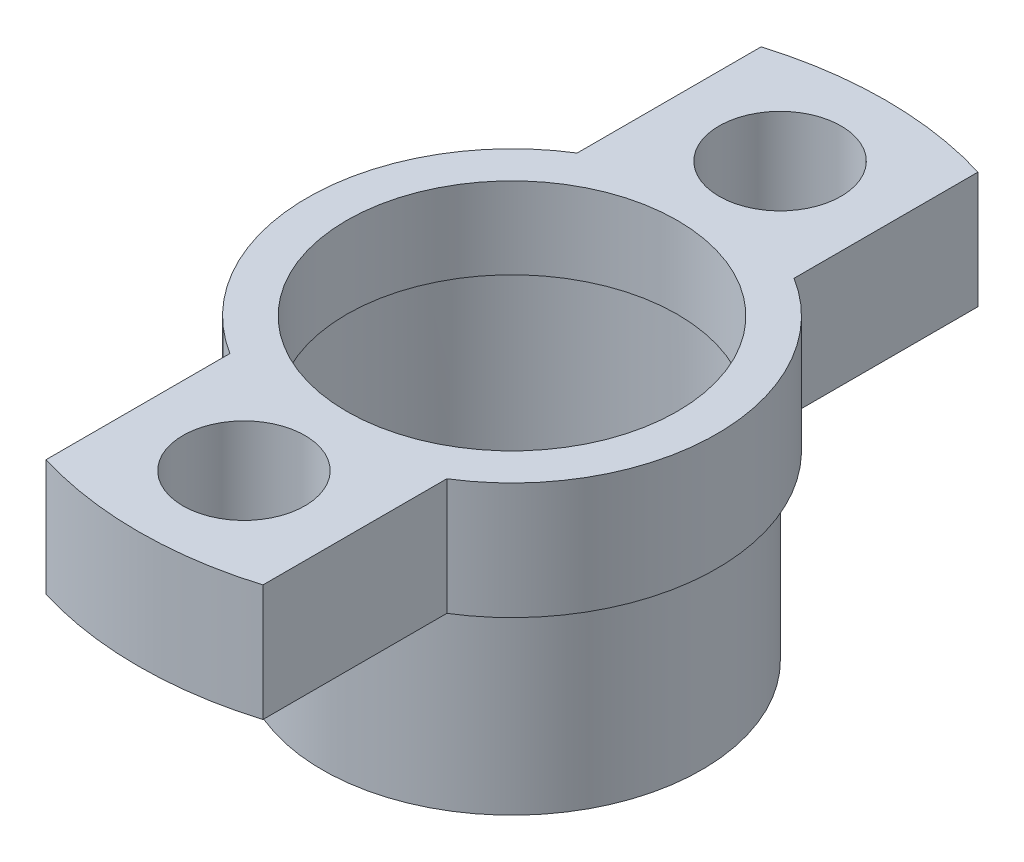
SolidWorks part; units mm, degrees
material "ABS"
ref_plane "Front Plane" through (0, 0, 0) normal (0, 0, 1) x (1, 0, 0)
ref_plane "Top Plane" through (0, 0, 0) normal (0, 1, 0) x (1, 0, 0)
ref_plane "Right Plane" through (0, 0, 0) normal (1, 0, 0) x (0, 0, -1)
sketch "Sketch2" plane through (0, 0, 0) normal (0, 1, 0) x (1, 0, 0)
  circle A0 centre (0, 0) radius 6.55
  circle A1 centre (0, 0) radius 5.8
  dimension "D1" = 13.1
  dimension "D2" = 0.75
extrude "Middle-core" add sketch "Sketch2" along normal blind 6 separate body
ref_plane "Plane for arms" through (0, 5, 0) normal (0, 1, 0) x (1, 0, 0)
sketch "Sketch3" plane through (0, 5, 0) normal (0, 1, 0) x (1, 0, 0)
  line L6 (-4, 5.1868) -> (-4, 13.1868)
  line L7 (-4, 13.1868) -> (4, 13.1868) construction
  line L8 (4, 13.1868) -> (4, 5.1868)
  line L9 (4, -5.1868) -> (4, -13.1868)
  line L10 (4, -13.1868) -> (-4, -13.1868) construction
  line L11 (-4, -13.1868) -> (-4, -5.1868)
  line L12 (0, -13.1868) -> (0, 13.1868) construction
  line L13 (0, -9.8868) -> (0, -13.1868) construction
  line L14 (0, 13.1868) -> (0, 9.8868) construction
  line L15 (0, 7.6368) -> (0, 6.5868) construction
  line L16 (0, 6.5868) -> (0, 12.1368) construction
  line L17 (0, 12.1368) -> (0, 13.1868) construction
  circle A1 centre (0, 9.8868) radius 2.25
  circle A3 centre (0, 0) radius 5.8
  arc A4 (4, -13.1868) -> (-4, -13.1868) centre (0, 0) cw
  arc A5 (-4, 5.1868) -> (-4, -5.1868) centre (0, 0) ccw
  circle A6 centre (0, 0) radius 6.55 construction
  arc A7 (4, -5.1868) -> (4, 5.1868) centre (0, 0) ccw
  circle A8 centre (0, -9.8868) radius 2.25
  circle A10 centre (0, 0) radius 5.8 construction
  arc A11 (-4, 13.1868) -> (4, 13.1868) centre (0, 0) cw
  point P3 (0, 9.8868)
  point P14 (0, 12.1368)
  point P16 (0, 7.6368)
  point P18 (0, -9.8868)
  point P26 (0, -12.1368)
  point P27 (0, -7.6368)
  point P29 (0, 6.5868)
  dimension "D2" = 4.5
  dimension "D1" = 8
  dimension "D3" = 3.3
extrude "Arms_insert-Fixing to guide part" add sketch "Sketch3" against normal blind 4.3
sketch "Sketch1" [suppressed] plane through (0, 0, 0) normal (0, 1, 0) x (1, 0, 0)
  line L0 (-6.2372, -2) -> (-10.2372, -2) construction
  line L1 (-10.2372, -2) -> (-10.2372, 2) construction
  line L2 (-10.2372, 2) -> (-6.2372, 2) construction
  line L3 (6.2372, 2) -> (10.2372, 2) construction
  line L4 (10.2372, 2) -> (10.2372, -2) construction
  line L5 (10.2372, -2) -> (6.2372, -2) construction
  line L6 (-6.55, 0) -> (-10.2372, 0) construction
  line L7 (-6.55, 0) -> (-3.55, 0) construction
  line L8 (-3.55, 0) -> (0, 0) construction
  line L9 (0, 0) -> (3.55, 0) construction
  line L10 (3.55, 0) -> (6.55, 0) construction
  line L11 (6.55, 0) -> (10.2372, 0) construction
  line L13 (-4, -2.1685) -> (-4, 2.1685)
  line L14 (-4, 2.1685) -> (4, 2.1685) construction
  line L15 (4, 2.1685) -> (4, -2.1685)
  line L16 (4, -5.1868) -> (4, -13.1868) construction
  line L17 (-4, -13.1868) -> (-4, -5.1868) construction
  line L18 (-4, -2.1685) -> (-4, -3.8474)
  line L19 (4, -2.1685) -> (4, -3.8474)
  line L20 (-4, 2.1685) -> (-4, 3.8474)
  line L21 (4, 2.1685) -> (4, 3.8474)
  circle A2 centre (0, 0) radius 6.55
  arc A3 (-6.2372, 2) -> (6.2372, 2) centre (0, 0) cw construction
  arc A4 (6.2372, -2) -> (-6.2372, -2) centre (0, 0) cw construction
  arc A5 (-4, -2.1685) -> (-4, 2.1685) centre (0, 0) cw construction
  arc A6 (4, 2.1685) -> (4, -2.1685) centre (0, 0) cw construction
  arc A7 (-4, -3.8474) -> (4, -3.8474) centre (0, 0) ccw
  arc A8 (-4, 3.8474) -> (4, 3.8474) centre (0, 0) cw
  point P15 (10.2372, 0)
  point P20 (-10.2372, 0)
  dimension "D4" = 5.55
  dimension "D1" = 13.1
  dimension "D2" = 4
  dimension "D3" = 4
  dimension "D5" = 1
extrude "Base-hole&toe" [suppressed] add sketch "Sketch1" along normal blind 2
ref_plane "Plane4" [suppressed] through (0, 2, 0) normal (0, 1, 0) x (1, 0, 0)
sketch "Sketch21" [suppressed] plane through (0, 2, 0) normal (0, 1, 0) x (1, 0, 0)
  line L1 (0, 0) -> (3.55, 0) construction
  line L2 (4.0623, -3) -> (12.55, -3)
  line L3 (12.55, -3) -> (12.55, 3)
  line L4 (12.55, 3) -> (4.0623, 3)
  line L5 (-4.0623, 3) -> (-12.55, 3)
  line L6 (-12.55, 3) -> (-12.55, -3)
  line L7 (-12.55, -3) -> (-4.0623, -3)
  line L8 (-12.55, 0) -> (-6.55, 0) construction
  line L9 (-9.55, 3) -> (-9.55, -3) construction
  line L10 (6.55, 0) -> (12.55, 0) construction
  line L11 (9.55, 3) -> (9.55, -3) construction
  line L14 (-6.55, 0) -> (-10.2372, 0) construction
  arc A0 (4.0623, -3) -> (4.0623, 3) centre (0, 0) ccw
  arc A1 (-4.0623, -3) -> (-4.0623, 3) centre (0, 0) cw
  circle A3 centre (-9.55, 0) radius 2
  circle A4 centre (9.55, 0) radius 2
  circle A7 centre (0, 0) radius 6.55 construction
  point P6 (-5.05, 0)
  point P38 (-11.55, 0)
extrude "Arms_hole-Fixing to support part" [suppressed] add sketch "Sketch21" against normal blind 2 separate body
sketch "Sketch22" plane through (0, 5, 0) normal (0, 1, 0) x (1, 0, 0)
  circle A0 centre (0, 0) radius 5.8
  circle A1 centre (0, 0) radius 5.3
  circle A2 centre (0, 0) radius 5.8 construction
  dimension "D1" = 10.6
extrude "Boss-Extrude1" [suppressed] add sketch "Sketch22" along normal up to surface (1 mm away)
sketch "Esquisse1" [suppressed] plane through (0, 0, 0) normal (1, 0, 0) x (0, 0, -1)
  line L1 (-21.6514, 20.4403) -> (22.7117, 20.4403)
  line L2 (-21.6514, 20.4403) -> (-21.6514, -7.7246)
  line L3 (-21.6514, -7.7246) -> (22.7117, -7.7246)
  line L4 (22.7117, 20.4403) -> (22.7117, -7.7246)
extrude "Enlèv. mat.-Extru.1" [suppressed] cut sketch "Esquisse1" along normal through all
sketch "Esquisse2" plane through (0, 0, 0) normal (0, -1, 0) x (1, 0, 0)
  circle A1 centre (0, 0) radius 7.55
  circle A3 centre (0, 0) radius 6.55
  circle A4 centre (0, 0) radius 6.55 construction
  dimension "D1" = 1
extrude "Boss.-Extru.1" add sketch "Esquisse2" against normal up to surface (5 mm away) up to face at (0, 5, -7.6368)
sketch "Esquisse3" plane through (0, 0, 0) normal (0, -1, 0) x (1, 0, 0)
  circle A0 centre (0, 0) radius 6.65
  circle A1 centre (0, 0) radius 7.55
  circle A2 centre (0, 0) radius 7.55 construction
  dimension "D1" = 0.9
extrude "Boss.-Extru.2" add sketch "Esquisse3" along normal blind 6
sketch "Esquisse4" plane through (0, 0.7, 0) normal (0, -1, 0) x (1, 0, 0)
  circle A0 centre (0, -9.8868) radius 2.75
  circle A1 centre (0, 9.8868) radius 2.75
  circle A2 centre (0, 9.8868) radius 2.25 construction
  circle A3 centre (0, 9.8868) radius 2.25 construction
  circle A4 centre (0, -9.8868) radius 2.25 construction
  dimension "D1" = 0.5
extrude "Enlèv. mat.-Extru.2" cut sketch "Esquisse4" along normal blind 4
sketch "Sketch23" [suppressed] plane through (0, -6, 0) normal (0, -1, 0) x (1, 0, 0)
  line L0 (25, 25) -> (-25, -25) construction
  line L1 (25, 25) -> (-25, 25)
  line L2 (25, 25) -> (25, -25)
  line L3 (25, -25) -> (-25, -25)
  line L4 (-25, 25) -> (-25, -25)
  line L5 (25, -25) -> (-25, 25) construction
  circle A0 centre (0, 0) radius 7.55
  circle A2 centre (0, 0) radius 7.55 construction
  point P9 (0, 0)
  dimension "D1" = 50
extrude "Cut-Extrude1" [suppressed] cut sketch "Sketch23" against normal blind 4
sketch "Sketch25" [suppressed] plane through (0, 0, 0) normal (0, 1, 0) x (1, 0, 0)
  circle A0 centre (11.5717, 8.8388) radius 7.8078
extrude "Cut-Extrude2" [suppressed] cut sketch "Sketch25" against normal through all both and the other way through all
sketch "Sketch26" plane through (0, -6, 0) normal (0, -1, 0) x (1, 0, 0)
  circle A0 centre (0, 0) radius 7.55
  circle A1 centre (0, 0) radius 6.65
extrude "Boss-Extrude4" add sketch "Sketch26" against normal up to surface (6.7 mm away) up to face at (0, 0.7, 9.1037)
sketch "Sketch27" plane through (0, -6, 0) normal (0, -1, 0) x (1, 0, 0)
  circle A0 centre (0, 0) radius 7.55
  circle A1 centre (0, 0) radius 7
  dimension "D1" = 14
extrude "Cut-Extrude3" cut sketch "Sketch27" against normal up to surface (6.7 mm away) up to face at (0, 0.7, 10.23)
sketch "Sketch28" plane through (0, -6, 0) normal (0, -1, 0) x (1, 0, 0)
  circle A0 centre (0, 0) radius 6.65
extrude "Cut-Extrude5" cut sketch "Sketch28" against normal blind 30
sketch "Sketch29" plane through (0, 5, 0) normal (0, 1, 0) x (1, 0, 0)
  circle A0 centre (0, 0) radius 6.65
  circle A1 centre (0, 0) radius 5.6
extrude "Boss-Extrude5" add sketch "Sketch29" against normal blind 3
sketch "Sketch30" plane through (0, 5, 0) normal (0, 1, 0) x (1, 0, 0)
  circle A0 centre (0, 0) radius 5.65
  dimension "D1" = 11.3
extrude "Cut-Extrude6" cut sketch "Sketch30" against normal blind 12
sketch "Sketch31" plane through (0, 2, 0) normal (0, -1, 0) x (1, 0, 0)
  circle A0 centre (0, 0) radius 5.675
  dimension "D1" = 11.35
extrude "Cut-Extrude7" cut sketch "Sketch31" against normal blind 10
sketch "Sketch32" plane through (0, 0.7, 0) normal (0, -1, 0) x (1, 0, 0)
  circle A0 centre (0, 0) radius 7.55
sketch "Sketch34" plane through (0, 5, 0) normal (0, 1, 0) x (1, 0, 0)
  circle A0 centre (0, 0) radius 6.1
  dimension "D1" = 12.2
extrude "Cut-Extrude9" cut sketch "Sketch34" against normal blind 10
equation "\"magnet_DI\"= 3mm'inner diameter of the o-ring magnet"
equation "\"magnet_DE\"= 8mm'external diameter of the o-ring magnet"
equation "\"magnet_H\"= 3mm'tall of the magnet"
equation "\"magnet_levitation_DI\"= 0mm'inner diameter of the o-ring magnet"
equation "\"magnet_levitation_DE\"= 1mm'external diameter of the o-ring magnet"
equation "\"magnet_levitation_H\"= 0.5mm'tall of the magnet"
equation "\"gap_magnet_H\"= 1mm'gap between the 2 magnets"
equation "\"plug_DI\"= 1.5mm'size of the inner extrude of the plug (finger contact)"
equation "\"coil_H\"= 8mm 'height coil"
equation "\"coil_W\"= 0.2mm 'width coil"
equation "\"mandrine_freegap\"= 0.2mm 'gap between the magnet and the mandrine. "
equation "\"mandrine_bottom_H\"= 0.5mm 'border of the bottom of the mandrine"
equation "\"mandrine_coilmagnet_wall\"= 0.15mm"
equation "\"mandrine_magnet_lev\"= 3mm' gap needed for the levitation of the rod"
equation "\"mandrine_border_H\"= 2mm 'border of the top of the mandrine"
equation "\"mandrine_epoxy_W\"= 0.5mm 'width epoxy"
equation "\"mandrine_DI\"= \"mandrine_freegap\"*2+\"magnet_DE\""
equation "\"mandrine_DE\"= (\"mandrine_epoxy_W\"+\"coil_W\"+\"mandrine_coilmagnet_wall\")*2+\"mandrine_DI\""
equation "\"mandrine_H\"= \"magnet_levitation_H\"+\"mandrine_magnet_lev\"+\"magnet_H\"+\"gap_magnet_H\"/2+\"coil_H\"/2+\"mandrine_border_H\""
equation "\"mandrine_hat_W\"= 1mm"
equation "\"tower_freegap\"= 1mm 'gap between the actuator and the tower"
equation "\"tower_DI\"= \"mandrine_DE\"+\"tower_freegap\""
equation "\"tower_W\"= 1mm'width of the tower"
equation "\"tower_link_H\"= 2mm"
equation "\"tower_link_W\"= 4mm"
equation "\"tower_channel_W\"= 1mm"
equation "\"tower_renforcement_H\"= 2mm"
equation "\"apex_tower_Dbase\"= 2.5mm 'diameter of the holes in order to curve"
equation "\"apex_tower_Rbase1\"= 0.75mm 'diameter of the holes in order to curve"
equation "\"apex_tower_Rbase2\"= 1mm 'diameter of the holes in order to curve"
equation "\"apex_tower_Rbase3\"= 1.25mm 'diameter of the holes in order to curve"
equation "\"apex_tower_holeOpening1\"= \"apex_tower_Rbase1\"*7/8"
equation "\"apex_tower_holeOpening2\"= \"apex_tower_Rbase2\"*7/8"
equation "\"apex_tower_holeOpening3\"= \"apex_tower_Rbase3\"*7/8"
equation "\"apex_tower_Hbase\"= 1mm 'gap between the bottom of the tower and the holes"
equation "\"apex_tower_hole\"= 4.5mm 'witdh of the hole"
equation "\"apex_tower_H\"= 0mm '\"mandrine_H\"-\"tower_link_H\""
equation "\"apex_tower_H2\"= \"apex_tower_H\"+7mm"
equation "\"actuator1.x\"= 42.59mm"
equation "\"actuator2.x\"= 80.026mm"
equation "\"actuator3.x\"= 0mm"
equation "\"actuator4.x\"= 14.55mm"
equation "\"actuator5.x\"= 14.557mm"
equation "\"actuator6.x\"= 12.497mm"
equation "\"actuator7.x\"= 27.494mm"
equation "\"actuator8.x\"= 39.75mm"
equation "\"actuator9.x\"= 41.5767mm"
equation "\"actuator10.x\"= 41.148mm"
equation "\"actuator11.x\"= 70.869mm"
equation "\"actuator12.x\"= 77.15mm"
equation "\"actuator13.x\"= 70.87mm"
equation "\"actuator14.x\"= 80.15mm"
equation "\"actuator15.x\"= 92.21mm"
equation "\"actuator16.x\"= 97.61mm"
equation "\"actuator17.x\"= 87.41mm"
equation "\"actuator18.x\"= 109.08mm"
equation "\"actuator19.x\"= 125.04mm"
equation "\"actuator20.x\"= 119.466mm"
equation "\"actuator21.x\"= 115.558mm"
equation "\"actuator22.x\"= 142.74mm"
equation "\"actuator23.x\"= 145.93mm"
equation "\"actuator24.x\"= 131.11mm"
equation "\"actuator1.y\"= 101.167mm"
equation "\"actuator2.y\"= 120.647mm"
equation "\"actuator3.y\"= 45.677mm"
equation "\"actuator4.y\"= 66.047mm"
equation "\"actuator5.y\"= 45.327mm"
equation "\"actuator6.y\"= 28.807mm"
equation "\"actuator7.y\"= 13.807mm"
equation "\"actuator8.y\"= 30.087mm"
equation "\"actuator9.y\"= 49.157mm"
equation "\"actuator10.y\"= 71.787mm"
equation "\"actuator11.y\"= 78.407mm"
equation "\"actuator12.y\"= 52.377mm"
equation "\"actuator13.y\"= 25.793mm"
equation "\"actuator14.y\"= 0.711mm"
equation "\"actuator15.y\"= 34.092mm"
equation "\"actuator16.y\"= 57.427mm"
equation "\"actuator17.y\"= 86.987mm"
equation "\"actuator18.y\"= 92.077mm"
equation "\"actuator19.y\"= 63.187mm"
equation "\"actuator20.y\"= 34.434mm"
equation "\"actuator21.y\"= 0mm"
equation "\"actuator22.y\"= 38.901mm"
equation "\"actuator23.y\"= 70.278mm"
equation "\"actuator24.y\"= 100.8741mm"
equation "\"actuator1.z\"= 45.834mm"
equation "\"actuator2.z\"= 37.834mm"
equation "\"actuator3.z\"= 13mm"
equation "\"actuator4.z\"= 33.9226mm"
equation "\"actuator5.z\"= 51.234mm"
equation "\"actuator6.z\"= 29.9773mm"
equation "\"actuator7.z\"= 49.434mm"
equation "\"actuator8.z\"= 31.7209mm"
equation "\"actuator9.z\"= 60.084mm"
equation "\"actuator10.z\"= 45.3632mm"
equation "\"actuator11.z\"= 42.0948mm"
equation "\"actuator12.z\"= 33.6927mm"
equation "\"actuator13.z\"= 48.7255mm"
equation "\"actuator14.z\"= 45.0141mm"
equation "\"actuator15.z\"= 63.034mm"
equation "\"actuator16.z\"= 50.5713mm"
equation "\"actuator17.z\"= 61.634mm"
equation "\"actuator18.z\"= 46.3531mm"
equation "\"actuator19.z\"= 57.834mm"
equation "\"actuator20.z\"= 58.534mm"
equation "\"actuator21.z\"= 44.984mm"
equation "\"actuator22.z\"= 45.5969mm"
equation "\"actuator23.z\"= 42.2671mm"
equation "\"actuator24.z\"= 33.4578mm"
equation "\"shape_freegap\"= \"tower_freegap\""
equation "\"shape_strip_witdh\"= 5mm"
equation "\"shape_holes_sweat_D\"= 2mm"
equation "\"shape_holes_actuator_D\"= \"magnet_DE\"+\"shape_freegap\"+1mm"
equation "\"shape_holes_actuator_extD\"= \"shape_holes_actuator_D\"+2*\"shape_strip_witdh\""
equation "\"shape_holes_wet_D\"= 2mm"
equation "\"amortisseur_Dext\"= 18mm"
equation "\"amortisseur_Din\"= 7mm"
equation "\"amortisseur_H\"= 20mm"
equation "\"amortisseur_prise_D\"= 10mm"
equation "\"amortisseur_bourlet_H\"= 0.5mm"
equation "\"fixation_prise_base_D\"= (\"amortisseur_prise_D\"+3)"
equation "\"fixation_prise_base_H\"= 1mm"
equation "\"fixation_prise_tete_D\"= (\"amortisseur_Dext\"+3)"
equation "\"fixation_prise_tete_H\"= 2.5mm"
equation "\"fixation_D\"= \"fixation_prise_tete_D\" + 2mm"
equation "\"fixation_H\"= \"fixation_prise_base_H\" + \"fixation_prise_tete_H\" + 3mm"
equation "\"fixation_zone_accroche_D\"= 3*\"fixation_D\""
equation "\"oring_R\"= 0.75mm"
equation "\"oring_R1\"= 0.25mm"
equation "\"oring_R2\"= 0.3mm"
equation "\"oring_R3\"= 0.75mm"
equation "\"guide_H1\"=4mm"
equation "\"guide_H2\"=1mm"
equation "\"guide_W1\"=1mm"
equation "\"guide_openAngle\"=360deg"
equation "\"guide_ecrou_DI\"=5mm"
equation "\"guide_ecrou_DE\"=8mm"
equation "\"guide_vis_DI\"=4mm"
equation "\"guide_rondelle_DE\"=9mm"
equation "\"D1@Sketch1\"=\"tower_DI\"+\"tower_W\"*2"
equation "\"D1@Base-hole&toe\" = \"tower_link_H\""
equation "\"D1@Middle-core\"=\"mandrine_H\"-\"mandrine_border_H\"/2-6"
equation "\"D4@Sketch1\"=(\"mandrine_DE\"+\"tower_freegap\")/2"
equation "\"D2@Sketch3\"=4.5"
equation "\"D2@Sketch2\"=\"tower_W\"*0.75"
equation "\"D1@Sketch22\"=\"mandrine_DE\"+\"tower_freegap\"/2"
equation "\"D1@Sketch2\"=\"tower_DI\"+\"tower_W\"*2"
